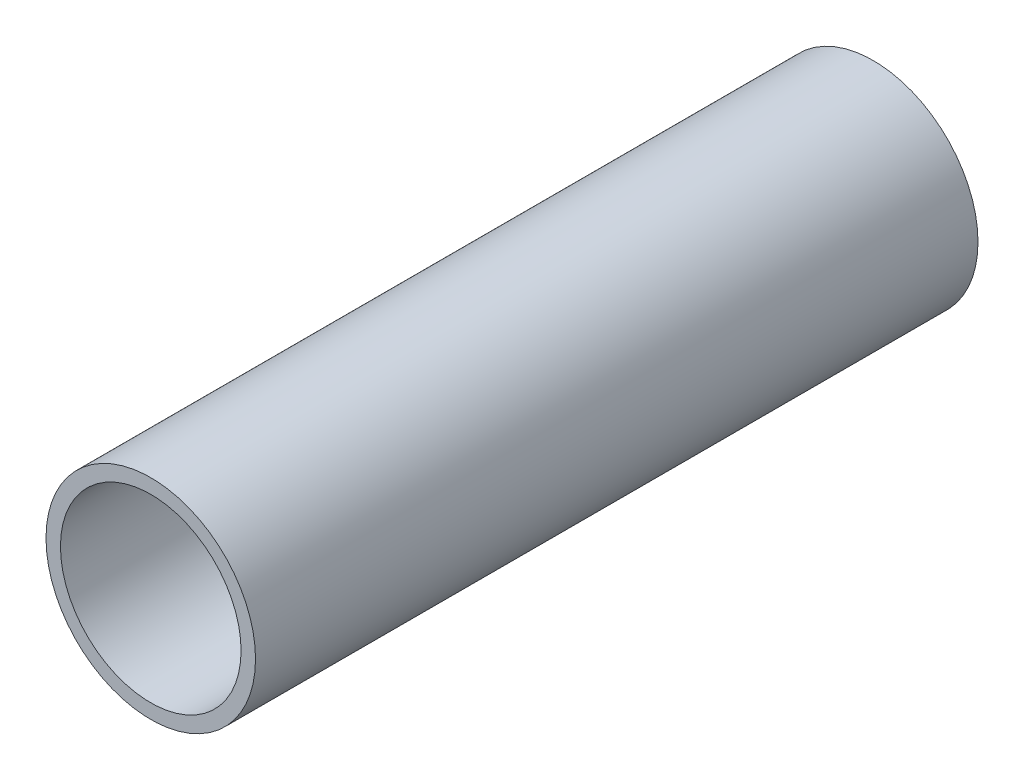
SolidWorks part; units mm, degrees
ref_plane "Front Plane" through (0, 0, 0) normal (0, 0, 1) x (1, 0, 0)
ref_plane "Top Plane" through (0, 0, 0) normal (0, 1, 0) x (1, 0, 0)
ref_plane "Right Plane" through (0, 0, 0) normal (1, 0, 0) x (0, 0, -1)
sketch "Sketch1" plane through (0, 0, 0) normal (0, 0, 1) x (1, 0, 0)
  circle A0 centre (0, 0) radius 12.5
  circle A1 centre (0, 0) radius 14.5
  dimension "D1" = 25
  dimension "D2" = 2
extrude "Boss-Extrude1" add sketch "Sketch1" along normal blind 100
